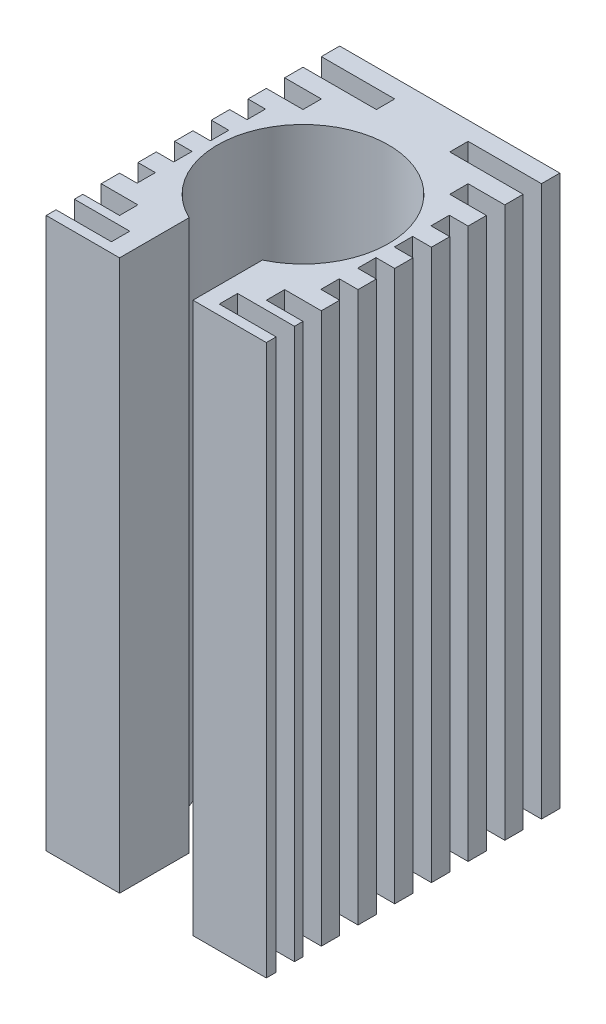
SolidWorks part; units mm, degrees
ref_plane "Front Plane" through (0, 0, 0) normal (0, 0, 1) x (1, 0, 0)
ref_plane "Top Plane" through (0, 0, 0) normal (0, 1, 0) x (1, 0, 0)
ref_plane "Right Plane" through (0, 0, 0) normal (1, 0, 0) x (0, 0, -1)
sketch "Sketch1" plane through (0, 0, 0) normal (0, 1, 0) x (1, 0, 0)
  line L1 (0, 0) -> (6, 0)
  line L2 (0, 0) -> (0, 8)
  line L3 (0, 8) -> (6, 8)
  line L4 (6, 0) -> (6, 8)
  dimension "D1" = 6
  dimension "D2" = 8
extrude "Boss-Extrude1" add sketch "Sketch1" along normal blind 15
sketch "Sketch2" plane through (0, 15, 0) normal (0, 1, 0) x (1, 0, 0)
  line L0 (3, 8) -> (3, 2.9378) construction
  line L1 (6, 8) -> (0, 8) construction
  line L2 (0, 0) -> (6, 0) construction
  line L3 (4, 0) -> (2, 0)
  line L4 (4, 0) -> (2, 0)
  line L5 (4, 0) -> (4, 1.8943)
  line L7 (2, 0) -> (2, 1.8943)
  arc A0 (4, 1.8943) -> (2, 1.8943) centre (3, 4) ccw
  dimension "D1" = 1
  dimension "D2" = 1
extrude "Cut-Extrude2" cut sketch "Sketch2" against normal blind 15
sketch "Sketch3" plane through (0, 15, 0) normal (0, 1, 0) x (1, 0, 0)
  line L0 (1, 0) -> (1, 8) construction
  line L1 (0, 0) -> (2, 0) construction
  line L2 (6, 8) -> (0, 8) construction
  line L3 (5, 0) -> (5, 8) construction
  line L4 (4, 0) -> (6, 0) construction
  line L5 (2, 0) -> (2, 8) construction
  line L6 (4, 0) -> (4, 8) construction
  line L7 (3, 8) -> (3, 6.3311) construction
  line L8 (6, 4) -> (0, 4) construction
  line L9 (6, 0) -> (6, 8) construction
  line L10 (0, 8) -> (0, 0) construction
  line L11 (5.489, 0) -> (5.489, 8) construction
  line L12 (4, 7.5) -> (6, 7.5)
  line L13 (4, 7.5) -> (4, 7)
  line L14 (4, 7) -> (6, 7)
  line L15 (6, 7.5) -> (6, 7)
  line L16 (2, 7) -> (0, 7)
  line L17 (2, 7) -> (2, 7.5)
  line L18 (2, 7.5) -> (0, 7.5)
  line L19 (0, 7) -> (0, 7.5)
  line L20 (5, 6.5) -> (6, 6.5)
  line L21 (5, 6.5) -> (5, 6)
  line L22 (5, 6) -> (6, 6)
  line L23 (6, 6.5) -> (6, 6)
  line L24 (0, 6.5) -> (1, 6.5)
  line L25 (0, 6.5) -> (0, 6)
  line L26 (0, 6) -> (1, 6)
  line L27 (1, 6.5) -> (1, 6)
  line L28 (0.4766, 8) -> (0.4766, 0)
  line L29 (4.4497, 8) -> (4.4497, 0)
  line L30 (5.489, 5.5) -> (6, 5.5)
  line L31 (5.489, 5.5) -> (5.489, 5)
  line L32 (5.489, 5) -> (6, 5)
  line L33 (6, 5.5) -> (6, 5)
  line L34 (5.489, 4.5) -> (6, 4.5)
  line L35 (5.489, 4.5) -> (5.489, 4)
  line L36 (5.489, 4) -> (6, 4)
  line L37 (6, 4.5) -> (6, 4)
  line L38 (0, 5.5) -> (0.4766, 5.5)
  line L39 (0, 5.5) -> (0, 5)
  line L40 (0, 5) -> (0.4766, 5)
  line L41 (0.4766, 5.5) -> (0.4766, 5)
  line L42 (0, 4.5) -> (0.4766, 4.5)
  line L43 (0, 4.5) -> (0, 4)
  line L44 (0, 4) -> (0.4766, 4)
  line L45 (0.4766, 4.5) -> (0.4766, 4)
  line L46 (6, 3.5) -> (5.489, 3.5)
  line L47 (6, 3.5) -> (6, 3)
  line L48 (6, 3) -> (5.489, 3)
  line L49 (5.489, 3.5) -> (5.489, 3)
  line L50 (0, 3.5) -> (0.4766, 3.5)
  line L51 (0, 3.5) -> (0, 3)
  line L52 (0, 3) -> (0.4766, 3)
  line L53 (0.4766, 3.5) -> (0.4766, 3)
  line L54 (0, 2.5) -> (0.4766, 2.5)
  line L55 (0, 2.5) -> (0, 2)
  line L56 (0, 2) -> (0.4766, 2)
  line L57 (0.4766, 2.5) -> (0.4766, 2)
  line L58 (5.489, 2.5) -> (6, 2.5)
  line L59 (5.489, 2.5) -> (5.489, 2)
  line L60 (5.489, 2) -> (6, 2)
  line L61 (6, 2.5) -> (6, 2)
  line L62 (6, 1.5) -> (5, 1.5)
  line L63 (6, 1.5) -> (6, 1)
  line L64 (6, 1) -> (5, 1)
  line L65 (5, 1.5) -> (5, 1)
  line L66 (1, 1) -> (0, 1)
  line L67 (1, 1) -> (1, 1.5)
  line L68 (1, 1.5) -> (0, 1.5)
  line L69 (0, 1) -> (0, 1.5)
  line L70 (1.5101, 8) -> (1.5101, 0)
  line L72 (6, 0.768) -> (4.4497, 0.768)
  line L73 (6, 0.768) -> (6, 0.268)
  line L74 (6, 0.268) -> (4.4497, 0.268)
  line L75 (4.4497, 0.768) -> (4.4497, 0.268)
  line L76 (0, 0.768) -> (1.5101, 0.768)
  line L77 (0, 0.768) -> (0, 0.268)
  line L78 (0, 0.268) -> (1.5101, 0.268)
  line L79 (1.5101, 0.768) -> (1.5101, 0.268)
  arc A0 (4, 1.8943) -> (2, 1.8943) centre (3, 4) ccw construction
  line M46 (6, 0) -> (6, 8)
  line M48 (0, 8) -> (0, 0)
  dimension "D1" = 0.5
  dimension "D2" = 0.5
  dimension "D3" = 2
  dimension "D4" = 0.5
  dimension "D5" = 0.5
  dimension "D6" = 0.5
  dimension "D7" = 0.5
  dimension "D8" = 0.5
  dimension "D9" = 0.5
  dimension "D10" = 0.5
  dimension "D11" = 0.5
  dimension "D12" = 0.5
  dimension "D13" = 0.5
  dimension "D14" = 0.5
  dimension "D15" = 0.5
  dimension "D16" = 0.5
  dimension "D17" = 0.5
  dimension "D18" = 0.5
  dimension "D19" = 0.5
  dimension "D20" = 0.5
  dimension "D21" = 0.5
  dimension "D22" = 0.5
  dimension "D23" = 0.5
  dimension "D24" = 0.5
  dimension "D25" = 0.5
  dimension "D26" = 0.5
  dimension "D27" = 0.5
  dimension "D28" = 0.5
  dimension "D29" = 0.5
  dimension "D30" = 0.5
  dimension "D31" = 0.5
extrude "Cut-Extrude3" cut sketch "Sketch3" against normal blind 15 contours L12 L29 L14 M46 | L29 L12 L13 L14 | L21 L22 L20 M46 | L31 L32 L30 M46 | L35 L36 L34 M46 | L46 L49 L48 M46 | L59 L60 L58 M46 | L62 L65 L64 M46 | L74 L72 L29 M46 | L28 L78 L70 L76 | L78 L28 L76 M48 | L28 L68 L66 M48 | L67 L68 L28 L66 | L56 L28 L54 M48 | L52 L28 L50 M48 | L44 L28 L42 M48 | L40 L28 L38 M48 | L28 L24 L26 M48 | L70 L18 L28 L16 | L28 L18 L16 M48 | L18 L70 L16 L17 | L24 L28 L26 L27
sketch "Sketch4" plane through (0, 15, 0) normal (0, 1, 0) x (1, 0, 0)
  line L0 (6, 8) -> (0, 8) construction
  line L1 (2.7043, 8) -> (3.3014, 8)
  line L2 (2.7043, 8) -> (2.7043, 6.9397)
  line L3 (2.7043, 6.9397) -> (3.3014, 6.9397)
  line L4 (3.3014, 8) -> (3.3014, 6.9397)
